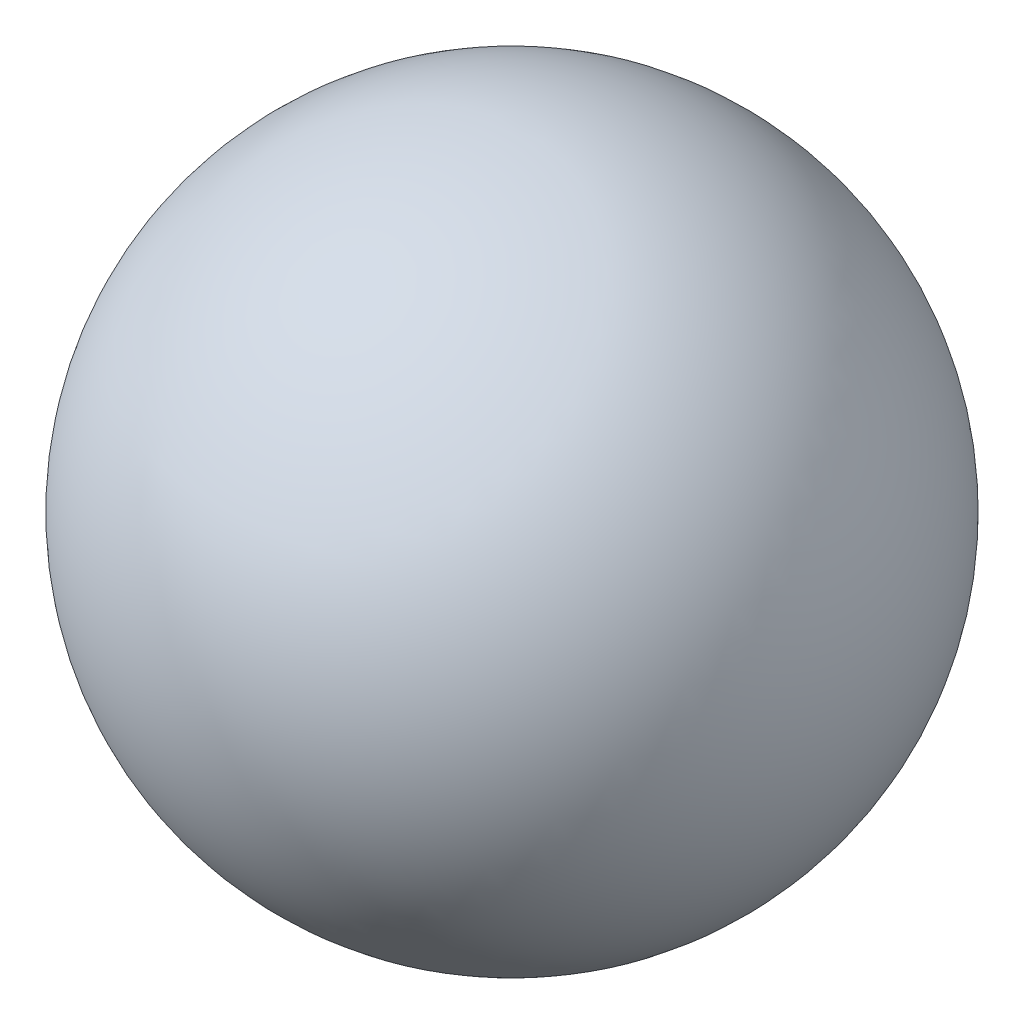
SolidWorks part; units mm, degrees
material "1.2083 (X40Cr14)"
ref_plane "Płaszczyzna przednia" through (0, 0, 0) normal (0, 0, 1) x (1, 0, 0)
ref_plane "Płaszczyzna górna" through (0, 0, 0) normal (0, 1, 0) x (1, 0, 0)
ref_plane "Płaszczyzna prawa" through (0, 0, 0) normal (1, 0, 0) x (0, 0, -1)
sketch "Szkic1" plane through (0, 0, 0) normal (0, 0, 1) x (1, 0, 0)
  line L0 (0, 0) -> (0, 0.8) construction
  line L1 (0, 0) -> (0, -0.8) construction
  line L2 (0, -0.8) -> (0, 0.8)
  arc A0 (0, 0.8) -> (0, -0.8) centre (0, 0) ccw
  circle A1 centre (0, 0) radius 0.8 construction
  dimension "D1" = 1.6
revolve "Obrót2" add sketch "Szkic1" angle 360 about L0
